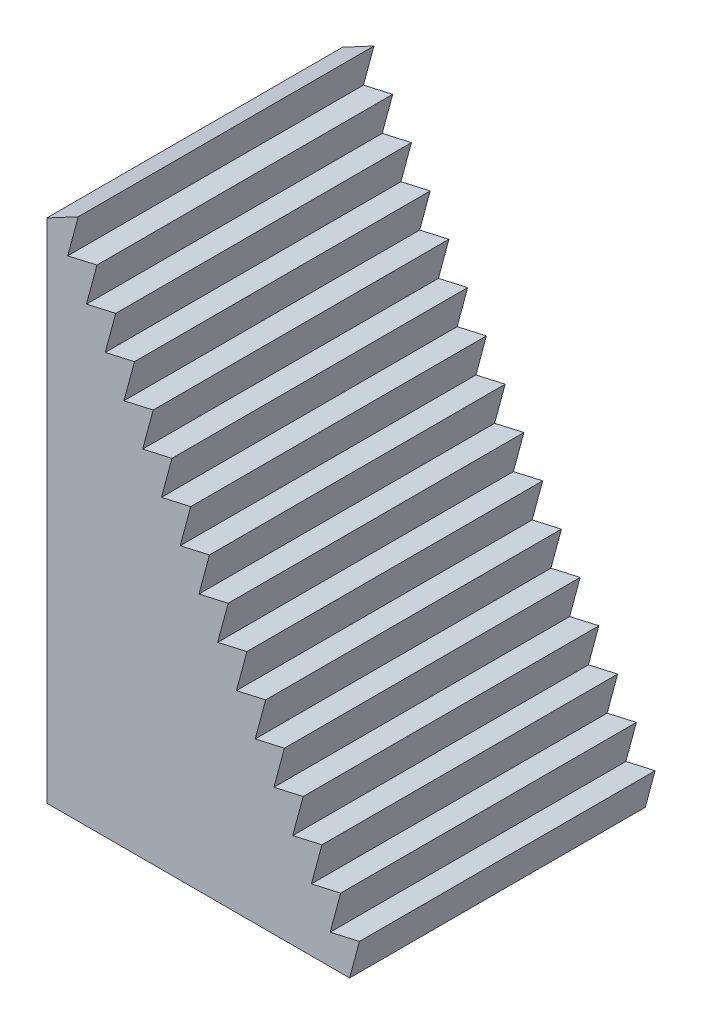
SolidWorks part; units mm, degrees
ref_plane "Front Plane" through (0, 0, 0) normal (0, 0, 1) x (1, 0, 0)
ref_plane "Top Plane" through (0, 0, 0) normal (0, 1, 0) x (1, 0, 0)
ref_plane "Right Plane" through (0, 0, 0) normal (1, 0, 0) x (0, 0, -1)
sketch "Sketch1" plane through (0, 0, 0) normal (0, 0, 1) x (1, 0, 0)
  line L0 (0, 42.926) -> (0, 0)
  line L1 (0, 0) -> (25.908, 0)
  line L2 (0, 42.926) -> (2.6557, 44.3423)
  line L6 (2.6557, 44.3423) -> (26.9179, 2.319)
  line L7 (25.908, 0) -> (26.9179, 2.319)
  dimension "D1" = 42.926
  dimension "D2" = 25.908
  dimension "D4" = 60
extrude "Boss-Extrude1" add sketch "Sketch1" along normal blind 25.0444
sketch "Sketch2" plane through (0, 0, 25.0444) normal (0, 0, 1) x (1, 0, 0)
  line L0 (2.6557, 44.3423) -> (1.7662, 41.0307)
  line L1 (1.7662, 41.0307) -> (4.2432, 41.5927)
  line L2 (26.9179, 2.319) -> (2.6557, 44.3423) construction
  line L3 (4.2432, 41.5927) -> (2.6557, 44.3423)
  dimension "D1" = 3.429
  dimension "D2" = 2.54
  dimension "D3" = 3.175
extrude "Cut-Extrude1" cut sketch "Sketch2" against normal through all
pattern_linear "LPattern1" count 17 spacing 3.175 along (0.5, -0.866, 0) of "Cut-Extrude1"
